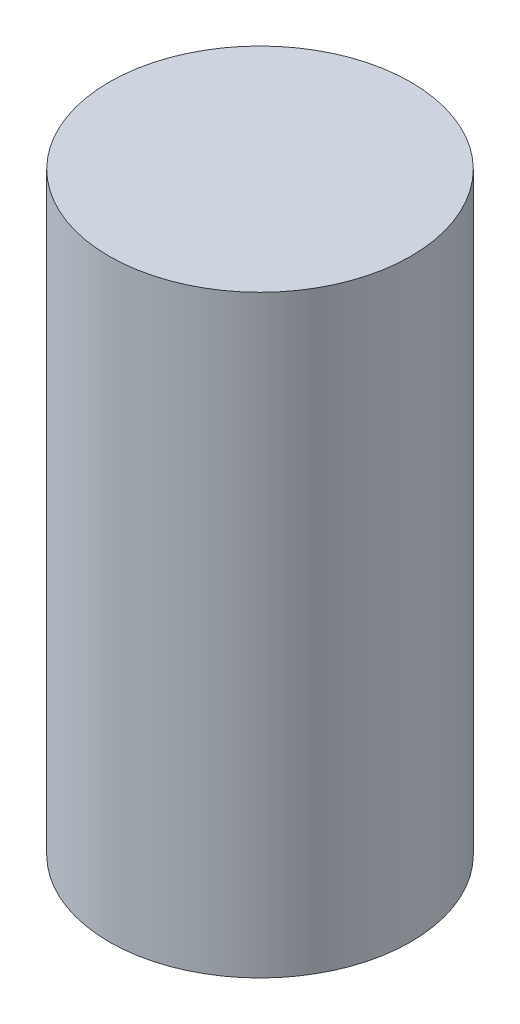
SolidWorks part; units mm, degrees
ref_plane "Front Plane" through (0, 0, 0) normal (0, 0, 1) x (1, 0, 0)
ref_plane "Top Plane" through (0, 0, 0) normal (0, 1, 0) x (1, 0, 0)
ref_plane "Right Plane" through (0, 0, 0) normal (1, 0, 0) x (0, 0, -1)
sketch "Sketch1" plane through (0, 0, 0) normal (0, 1, 0) x (1, 0, 0)
  circle A0 centre (0, 0) radius 2.54
  dimension "D1" = 5.08
extrude "Boss-Extrude1" add sketch "Sketch1" along normal blind 10
equation "\"pin diamiter\"= 5mm"
equation "\"D1@Sketch1\"=\"pin diamiter\""
